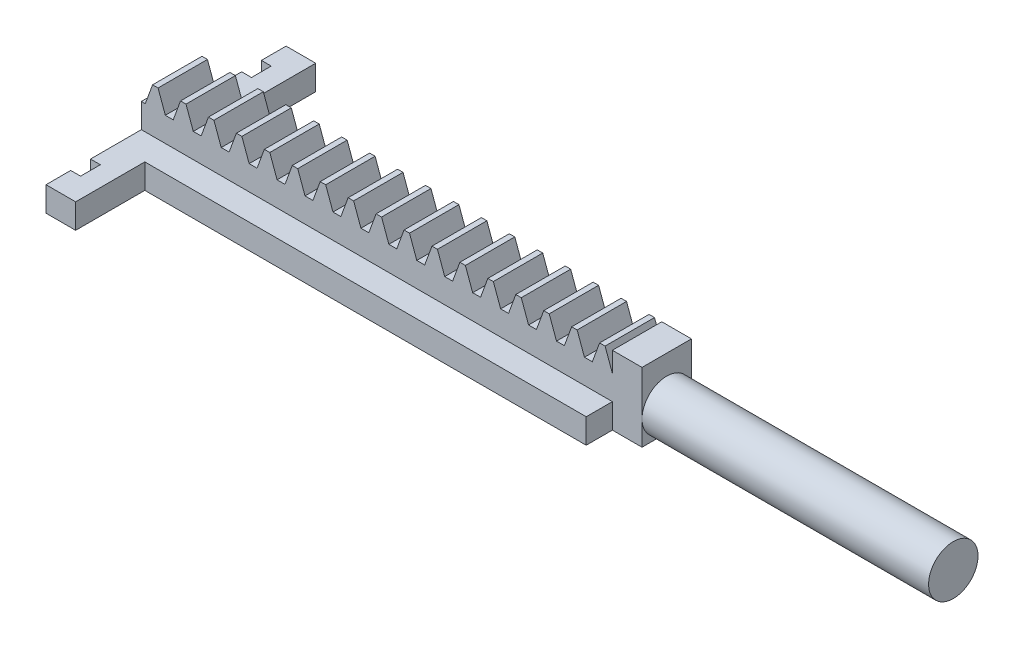
SolidWorks part; units mm, degrees
extrude "Blank" add sketch "BlankSke" against normal blind 5
sketch "BlankSke" plane through (0, 0, 0) normal (0, 0, 1) x (1, 0, 0)
  line L1 (0, 0) -> (47.667, 0)
  line L2 (0, 0) -> (0, 7)
  line L3 (0, 7) -> (47.667, 7)
  line L4 (47.667, 0) -> (47.667, 7)
  dimension "Length" = 47.667
  dimension "Blank_height" = 7
ref_plane "Plane1" through (0, 0, 0) normal (0, 0, 1) x (1, 0, 0)
ref_plane "Plane2" through (0, 0, 0) normal (0, 1, 0) x (1, 0, 0)
ref_plane "Plane3" through (0, 0, 0) normal (1, 0, 0) x (0, 0, -1)
other "Configuration Table"
sketch "HoldingSke" plane through (0, 0, 0) normal (0, 1, 0) x (1, 0, 0)
  line L0 (0, 0) -> (0.1546, 1.1003)
  line L1 (-15, 0) -> (100, 0) construction
  line L2 (0, 0) -> (-2.1039, 2.3779)
  line L3 (0, 0) -> (-11.863, 4.5341)
  line L4 (0, 0) -> (7.9495, 3.3743)
  line L5 (0, 0) -> (-23.7986, -8.8762)
  line L6 (0, 0) -> (-10.5278, -7.1032)
  line L9 (-71.009, 38.7566) -> (-14.6274, 59.2778)
  line L10 (-76.2, 3.2779) -> (-66.2, 3.2779)
  line L11 (0, 0) -> (-10, 0)
  line L12 (-76.2, 101.6) -> (-76.166, 101.6)
  line L13 (24.9733, 27.94) -> (52.9518, 28.4284)
  line L14 (24.9733, 27.94) -> (24.9743, 27.94)
  line L15 (24.9733, 27.94) -> (100.4006, 29.5858)
  circle A0 centre (0, 0) radius 19.05
  circle A1 centre (0, 0) radius 5
  circle A2 centre (0, 0) radius 12.7
  dimension "MPH" = 10
  dimension "Diameter" = 38.1
  dimension "Num_teeth" = 23
  dimension "Pitch" = 1.1111
  dimension "Show_teeth" = 998
  dimension "Thickness" = 12.7
  dimension "Ap" = 20
  dimension "Pitch_height" = 10
  dimension "Width" = 10
  dimension "Backlash" = 0.034
  dimension "Addendum_fac" = 1
  dimension "Dedendum_fac" = 1.25
  dimension "Clearance_fac" = 0.25
  dimension "Dedendum_add" = 0.001
  dimension "Length" = 60
  dimension "Module" = 0.9
sketch "TooCutSkeIll" plane through (0, 0, 0) normal (0, 0, 1) x (1, 0, 0)
  line L0 (0.2917, 6.9763) -> (-0.4535, 9.0237)
  line L1 (-0.2411, 8.875) -> (0.2411, 8.875)
  line L2 (0.4535, 9.0237) -> (-0.2917, 6.9763)
  line L3 (47.667, 7) -> (0, 7) construction
  line L4 (0, 0) -> (0, 64.897) construction
  line L5 (-13.208, 10) -> (12.954, 10) construction
  line L6 (0, 0) -> (47.667, 0) construction
  line L7 (0.8089, 10) -> (0.8089, 48.7463) construction
  line L8 (-0.8089, 10) -> (-0.8089, 48.7463) construction
  line L9 (-0.2578, 7) -> (-0.2578, 10.9254)
  line L10 (0.2578, 7) -> (0.2578, 10.9254)
  line L11 (0.2578, 10.9254) -> (-0.2578, 10.9254)
  arc A0 (0.2411, 8.875) -> (0.4535, 9.0237) centre (0.2411, 9.101) ccw
  arc A1 (-0.4535, 9.0237) -> (-0.2411, 8.875) centre (-0.2411, 9.101) ccw
  arc A2 (-0.2578, 7) -> (-0.2917, 6.9763) centre (-0.2578, 6.964) ccw
  arc A3 (0.2917, 6.9763) -> (0.2578, 7) centre (0.2578, 6.964) ccw
  dimension "Pitch_height" = 10
  dimension "Addendum_plus" = 0.9254
  dimension "Pressure_angle" = 20
  dimension "Gap_width" = 1.6177
  dimension "Dedendum" = 1.125
extrude "ToothCutIll" [suppressed] cut sketch "TooCutSkeIll" against normal through all
sketch "TooCutSkeSim" plane through (0, 0, 0) normal (0, 0, 1) x (1, 0, 0)
  line L0 (0.3994, 4.975) -> (-0.3994, 4.975)
  line L1 (1.1457, 7.0254) -> (0.3994, 4.975)
  line L2 (0, 17.4625) -> (0, 53.467) construction
  line L3 (1.1457, 7.0254) -> (-1.1457, 7.0254)
  line L6 (-1.1457, 7.0254) -> (-0.3994, 4.975)
  line L9 (-0.8089, 6.1) -> (0.8089, 6.1) construction
  line L10 (0, 0) -> (47.667, 0) construction
  line L11 (0.8089, 6.1) -> (0.8089, 53.467) construction
  line L12 (-0.8089, 6.1) -> (-0.8089, 53.467) construction
  dimension "Addendum_plus" = 0.9254
  dimension "Pitch_height" = 6.1
  dimension "Pressure_angle" = 20
  dimension "Gap_width" = 1.6177
  dimension "Dedendum" = 1.125
extrude "ToothCutSim" cut sketch "TooCutSkeSim" against normal through all
pattern_linear "TeethCuts" count 18 spacing 2.8274 along (1, 0, 0) of "ToothCutSim"
sketch "Sketch1" plane through (47.667, 0, 0) normal (1, 0, 0) x (0, 0, -1)
  line L0 (2.5, 4.975) -> (2.5, 0) construction
  line L1 (0, 4.975) -> (5, 4.975) construction
  line L2 (5, 0) -> (0, 0) construction
  line L3 (0, 2.4875) -> (5, 2.4875) construction
  line L4 (0, 0) -> (0, 4.975) construction
  line L5 (5, 0) -> (5, 4.975) construction
  circle A0 centre (2.5, 2.4875) radius 2.5
  dimension "D1" = 5
extrude "Boss-Extrude1" add sketch "Sketch1" along normal blind 32
sketch "Sketch2" plane through (0, 0, 0) normal (-1, 0, 0) x (0, 0, 1)
  line L0 (-2.5, 4.975) -> (-2.5, 0) construction
  line L1 (-7.6475, 2.5) -> (-5, 2.5)
  line L2 (-7.6475, 2.5) -> (-7.6475, 0)
  line L3 (-7.6475, 0) -> (-5, 0)
  line L4 (-5, 2.5) -> (-5, 0)
  line L5 (-7.6475, 2.5) -> (-5, 0) construction
  line L6 (-7.6475, 0) -> (-5, 2.5) construction
  line L7 (-5, 4.975) -> (0, 4.975) construction
  line L8 (-5, 0) -> (0, 0) construction
  line L9 (2.6475, 0) -> (0, 0)
  line L10 (0, 2.5) -> (0, 0)
  line L11 (2.6475, 2.5) -> (0, 2.5)
  line L12 (2.6475, 2.5) -> (2.6475, 0)
  point P0 (-6.3237, 1.25)
  dimension "D1" = 2.5
extrude "Boss-Extrude2" add sketch "Sketch2" against normal up to surface (47.667 mm away) up to face at (47.667, 0.6847, -4.4096)
sketch "Sketch3" plane through (47.667, 0, 0) normal (1, 0, 0) x (0, 0, -1)
  line L1 (0, 0) -> (5, 0)
  line L2 (0, 0) -> (0, 7)
  line L3 (0, 7) -> (5, 7)
  line L4 (5, 0) -> (5, 7)
  line L5 (0, 2.5) -> (0, 4.975) construction
  line L6 (5, 2.5) -> (5, 4.975) construction
  dimension "D1" = 7
extrude "Boss-Extrude3" add sketch "Sketch3" along normal blind 3
sketch "Sketch4" plane through (0, 0, -7.6475) normal (0, 0, -1) x (-1, 0, 0)
  line L0 (-47.667, 0) -> (0, 0) construction
  line L1 (-3, 2.5) -> (0, 2.5)
  line L2 (-3, 2.5) -> (-3, 0)
  line L3 (-3, 0) -> (0, 0)
  line L4 (0, 2.5) -> (0, 0)
  line L5 (-3, 2.5) -> (0, 0) construction
  line L6 (-3, 0) -> (0, 2.5) construction
  line L7 (-47.667, 2.5) -> (0, 2.5) construction
  line L8 (0, 2.5) -> (0, 0) construction
  point P0 (-1.5, 1.25)
  dimension "D1" = 3
extrude "Boss-Extrude4" add sketch "Sketch4" along normal blind 7
ref_plane "Plane4" through (0, 0, -2.5) normal (0, 0, -1) x (-1, 0, 0)
mirror "Mirror1" about plane through (0, 0, -2.5) normal (0, 0, -1) of "Boss-Extrude4"
sketch "Sketch5" plane through (0, 0, 0) normal (-1, 0, 0) x (0, 0, 1)
  line L0 (-14.6475, 0) -> (9.6475, 0) construction
  line L1 (-12.1475, 2.5) -> (-10.1475, 2.5)
  line L2 (-12.1475, 2.5) -> (-12.1475, 0)
  line L3 (-12.1475, 0) -> (-10.1475, 0)
  line L4 (-10.1475, 2.5) -> (-10.1475, 0)
  line L5 (-12.1475, 2.5) -> (-10.1475, 0) construction
  line L6 (-12.1475, 0) -> (-10.1475, 2.5) construction
  line L7 (-5, 2.5) -> (-14.6475, 2.5) construction
  line L8 (-14.6475, 0) -> (-14.6475, 2.5) construction
  point P0 (-11.1475, 1.25)
  dimension "D1" = 2.5
  dimension "D2" = 2
extrude "Cut-Extrude1" cut sketch "Sketch5" against normal blind 1
ref_plane "Plane5" through (0, 0, -2.5) normal (0, 0, -1) x (-1, 0, 0)
mirror "Mirror2" about plane through (0, 0, -2.5) normal (0, 0, -1) of "Cut-Extrude1"
equation "' \"Module@HoldingSke\" = 6.35"
equation "' \"Num_teeth@HoldingSke\" = 12"
equation "' \"Ap@HoldingSke\" =  20"
equation "' \"Ap@HoldingSke\" = 20"
equation "' \"Width@HoldingSke\" = 0.25 * 25.4"
equation "' \"Show_teeth@HoldingSke\" = 500"
equation "' \"Backlash@HoldingSke\" = 0.009 * 25.4"
equation "' \"Addendum_fac@HoldingSke\" = 1.0"
equation "' \"Dedendum_fac@HoldingSke\" = 1.25"
equation "' \"Dedendum_add@HoldingSke\" = 0.00005 * 25.4"
equation "' \"Clearance_fac@HoldingSke\" = 0.25"
equation "' \"Pitch_height@HoldingSke\" = 1 * 25.4"
equation "' \"Length@HoldingSke\" = 4.71 * 25.4"
equation "\"Pitch@HoldingSke\" = 1 / \"Module@HoldingSke\""
equation "\"MPH@HoldingSke\" = \"Dedendum_fac@HoldingSke\" / \"Pitch@HoldingSke\" + 2 * \"Dedendum_add@HoldingSke\" + 0.002 * 25.4"
equation "\"MPH@HoldingSke\" = ((sgn( \"MPH@HoldingSke\" - \"Pitch_height@HoldingSke\")+1)*( \"MPH@HoldingSke\" - \"Pitch_height@HoldingSke\"))/2 + \"Pitch_height@HoldingSke\""
equation "\"Pressure_angle@TooCutSkeIll\" = \"Ap@HoldingSke\""
equation "\"Addendum_plus@TooCutSkeIll\" =  \"Addendum_fac@HoldingSke\"  / \"Pitch@HoldingSke\" + 0.001 *25.4"
equation "\"Dedendum@TooCutSkeIll\" = \"Dedendum_fac@HoldingSke\"  / \"Pitch@HoldingSke\""
equation "\"Pitch_height@TooCutSkeIll\" =  \"MPH@HoldingSke\""
equation "\"Gap_width@TooCutSkeIll\" = 3.14159265 / 2 / \"Pitch@HoldingSke\" + 6 * \"Backlash@HoldingSke\""
equation "\"Pressure_angle@TooCutSkeSim\" = \"Ap@HoldingSke\""
equation "\"Addendum_plus@TooCutSkeSim\" =  \"Addendum_fac@HoldingSke\"  / \"Pitch@HoldingSke\" + 0.001 * 25.4"
equation "\"Dedendum@TooCutSkeSim\" = \"Dedendum_fac@HoldingSke\"  / \"Pitch@HoldingSke\""
equation "\"Gap_width@TooCutSkeSim\" = 3.14159265 / 2 / \"Pitch@HoldingSke\" + 6 * \"Backlash@HoldingSke\""
equation "\"Root_fillet@TooCutSkeIll\" = \"Clearance_fac@HoldingSke\" / \"Pitch@HoldingSke\" + \"Dedendum_add@HoldingSke\""
equation "\"Break_rad@TooCutSkeIll\" = 0.02 / \"Pitch@HoldingSke\" * 2"
equation "\"Linear_pitch@TeethCuts\" = 3.14159265 / \"Pitch@HoldingSke\""
equation "\"Num_teeth@HoldingSke\" = int( ( \"Length@HoldingSke\" + 0 ) / (3.14159265 / \"Pitch@HoldingSke\")) + 0.9999  + 1"
equation " \"Num_teeth@TeethCuts\" = ((sgn( \"Num_teeth@TeethCuts\" - \"Num_teeth@HoldingSke\" )-1)*( \"Num_teeth@TeethCuts\" - \"Num_teeth@HoldingSke\" ))/-2+ \"Num_teeth@HoldingSke\""
equation " \"Num_teeth@TeethCuts\" = ((sgn( \"Num_teeth@TeethCuts\" - 2.0)+1)*( \"Num_teeth@TeethCuts\" - 2.0))/2 +2.0"
